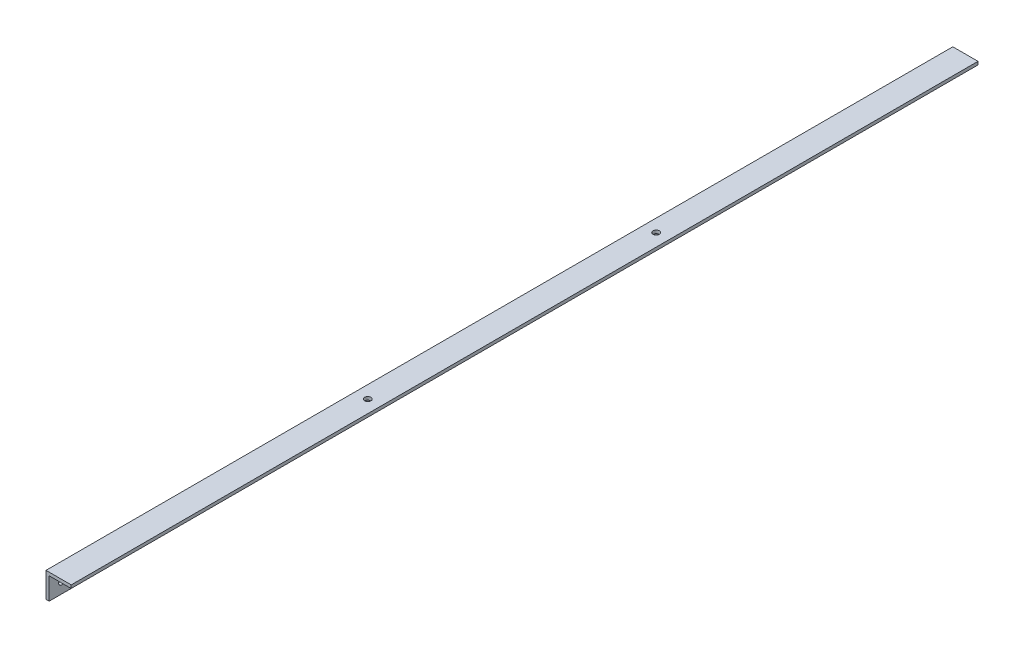
SolidWorks part; units mm, degrees
ref_plane "Front Plane" through (0, 0, 0) normal (0, 0, 1) x (1, 0, 0)
ref_plane "Top Plane" through (0, 0, 0) normal (0, 1, 0) x (1, 0, 0)
ref_plane "Right Plane" through (0, 0, 0) normal (1, 0, 0) x (0, 0, -1)
sketch "Sketch1" plane through (0, 0, 0) normal (0, 0, 1) x (1, 0, 0)
  line L0 (0, 0) -> (0, 25.4)
  line L1 (0, 25.4) -> (25.4, 25.4)
  line L2 (3.175, 0) -> (3.175, 22.225)
  line L3 (3.175, 22.225) -> (25.4, 22.225)
  line L4 (25.4, 22.225) -> (25.4, 25.4)
  line L5 (3.175, 0) -> (0, 0)
  dimension "D1" = 25.4
  dimension "D2" = 25.4
  dimension "D3" = 3.175
extrude "Boss-Extrude1" add sketch "Sketch1" along normal blind 914.4
sketch "Sketch2" plane through (0, 0, 0) normal (-1, 0, 0) x (0, 0, 1)
  line L0 (457.2, 0) -> (457.2, 25.4) construction
  line L1 (914.4, 0) -> (0, 0) construction
  line L2 (914.4, 25.4) -> (0, 25.4) construction
  line L3 (457.2, 12.7) -> (705.261, 12.7) construction
  line L4 (457.2, 12.7) -> (290.2039, 12.7) construction
  circle A0 centre (338.1375, 12.7) radius 3.175
  circle A1 centre (576.2625, 12.7) radius 3.175
  dimension "D1" = 6.35
  dimension "D2" = 119.0625
extrude "Cut-Extrude1" cut sketch "Sketch2" against normal blind 914.4
sketch "Sketch3" plane through (0, 25.4, 0) normal (0, 1, 0) x (1, 0, 0)
  circle A0 centre (12.7, -602.5917) radius 3.175
  circle A1 centre (12.7, -311.8083) radius 3.175
  dimension "D1" = 6.35
extrude "Cut-Extrude2" cut sketch "Sketch3" against normal through all
sketch "Sketch4" plane through (3.175, 0, 0) normal (1, 0, 0) x (0, 0, -1)
  circle A0 centre (-901.7, 11.1125) radius 3.175
  circle A1 centre (-12.7, 11.1125) radius 3.175
extrude "Cut-Extrude3" cut sketch "Sketch4" against normal up to next
